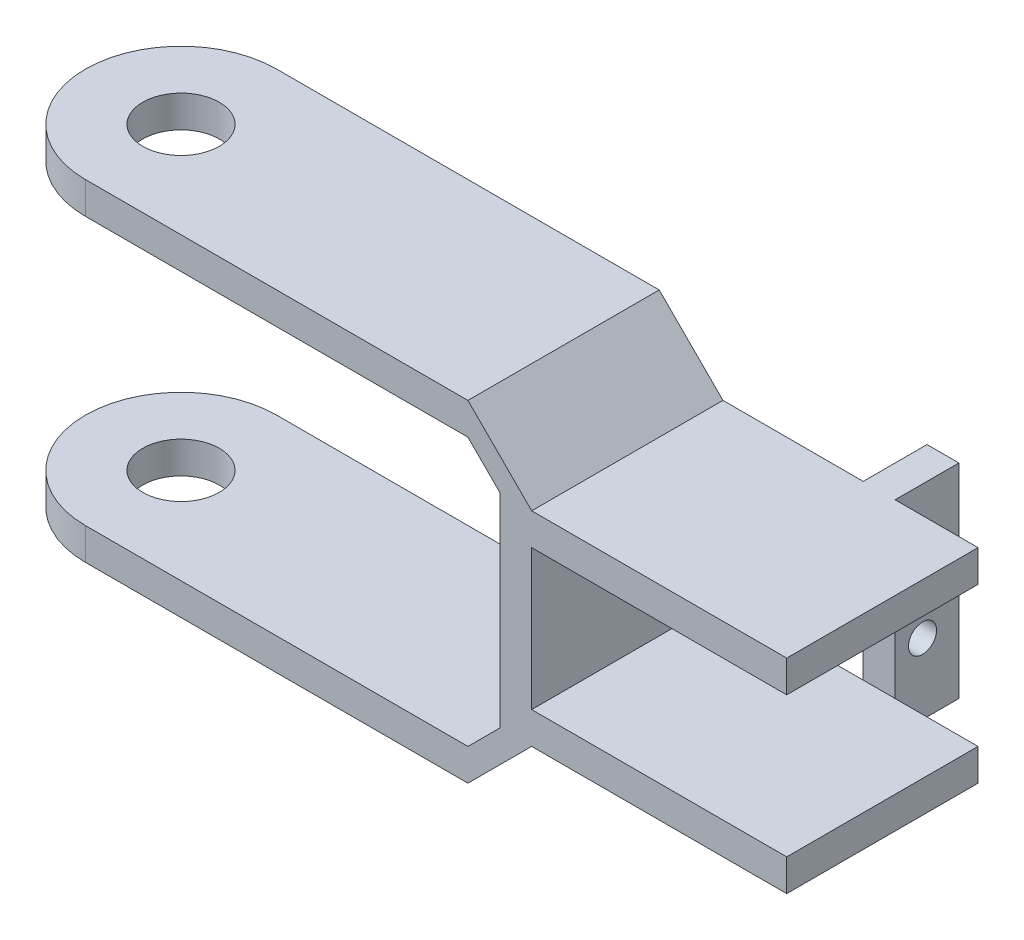
SolidWorks part; units mm, degrees
ref_plane "Front Plane" through (0, 0, 0) normal (0, 0, 1) x (1, 0, 0)
ref_plane "Top Plane" through (0, 0, 0) normal (0, 1, 0) x (1, 0, 0)
ref_plane "Right Plane" through (0, 0, 0) normal (1, 0, 0) x (0, 0, -1)
sketch "Sketch1" plane through (0, 0, 0) normal (0, 1, 0) x (1, 0, 0)
  line L3 (0, 15) -> (60, 15)
  line L4 (0, -15) -> (60, -15)
  line L5 (60, -15) -> (60, 15)
  circle A0 centre (0, 0) radius 6
  arc A2 (0, 15) -> (0, -15) centre (0, 0) ccw
extrude "Boss-Extrude4" add sketch "Sketch1" along normal blind 5
sketch "Sketch8" plane through (0, 0, 15) normal (0, 0, 1) x (1, 0, 0)
  line L0 (0, 0) -> (0, -21) construction
  line L1 (0, -21) -> (118.0272, -21) construction
  line L2 (60, 0) -> (60, -21) construction
  line L3 (60, -21) -> (70, -21) construction
  line L4 (70, -21) -> (70, -10) construction
  line L5 (60, 0) -> (70, -10)
  line L6 (70, -10) -> (110, -10)
  line L7 (110, -10) -> (110, -5)
  line L8 (110, -5) -> (70, -5)
  line L9 (70, -5) -> (60, 5)
  line L10 (60, 5) -> (60, 0)
extrude "Boss-Extrude5" add sketch "Sketch8" against normal blind 30
sketch "Sketch9" plane through (0, 0, 15) normal (0, 0, 1) x (1, 0, 0)
  line L0 (110, -10) -> (110, -21) construction
  line L1 (70, -10) -> (70, -21)
  line L2 (70, -21) -> (65, -21)
  line L3 (65, -21) -> (65, -5)
  line L4 (60, 0) -> (70, -10) construction
  line L5 (65, -5) -> (70, -10)
extrude "Boss-Extrude6" add sketch "Sketch9" against normal blind 30
mirror "Mirror3" about plane through (70, -21, -15) normal (0, -1, 0) of "Boss-Extrude6"
ref_plane "Plane2" through (0, -21, 0) normal (0, -1, 0) x (-1, 0, 0)
sketch "Sketch10" plane through (0, 0, 15) normal (0, 0, 1) x (1, 0, 0)
  line L0 (70, -21) -> (-15.976, -21) construction
  line L1 (70, -32) -> (70, -10) construction
  line L2 (-16.5, -21) -> (16.5, -21) construction
ref_plane "Plane3" through (0, -42, 0) normal (0, -1, 0) x (-1, 0, 0)
sketch "Sketch11" plane through (0, -42, 0) normal (0, -1, 0) x (-1, 0, 0)
  line L0 (0, 15) -> (-60, 15)
  line L1 (-60, 15) -> (-60, -15)
  line L2 (-60, -15) -> (0, -15)
  arc A0 (0, -15) -> (0, 15) centre (0, 0) ccw
  circle A1 centre (0, 0) radius 6
extrude "Boss-Extrude7" add sketch "Sketch11" along normal blind 5 separate body
sketch "Sketch12" plane through (0, 0, -15) normal (0, 0, -1) x (-1, 0, 0)
  line L2 (-70, -10) -> (-110, -10) construction
  line L4 (-110, -5) -> (-70, -5) construction
  line L6 (-70, -5) -> (-60, 5) construction
  line L8 (-60, 0) -> (-65, -5) construction
  line L12 (-16.5, -21) -> (16.5, -21) construction
  line L13 (-70, -32) -> (-65, -37)
  line L14 (-60, -47) -> (-60, -42)
  line L15 (-60, -42) -> (-65, -37)
  line L16 (-70, -37) -> (-60, -47)
  line L17 (-110, -37) -> (-70, -37)
  line L18 (-70, -32) -> (-110, -32)
  line L19 (-110, -32) -> (-110, -37)
extrude "Boss-Extrude8" add sketch "Sketch12" against normal blind 30
sketch "Sketch13" plane through (0, 0, -15) normal (0, 0, -1) x (-1, 0, 0)
  line L0 (-110, -10) -> (-97, -10) construction
  line L1 (-70, -10) -> (-110, -10) construction
  line L2 (-97, -10) -> (-97, -37)
  line L3 (-110, -37) -> (-70, -37) construction
  line L4 (-97, -37) -> (-92, -37)
  line L5 (-92, -37) -> (-92, -5)
  line L6 (-110, -5) -> (-70, -5) construction
  line L7 (-92, -5) -> (-97, -5)
  line L8 (-97, -5) -> (-97, -10)
extrude "Boss-Extrude9" add sketch "Sketch13" along normal blind 10
sketch "Sketch14" plane through (97, 0, 0) normal (1, 0, 0) x (0, 0, -1)
  line L0 (20.5314, -21) -> (19.3, -21) construction
  line L1 (15, -10) -> (15, -32) construction
  line L2 (15, -15) -> (19.3, -15) construction
  line L3 (25, -21) -> (20.5314, -21) construction
  line L4 (25, -5) -> (25, -37) construction
  line L5 (-16.5, -21) -> (16.5, -21) construction
  line L6 (19.3, -21) -> (19.3, -16.05) construction
  circle A2 centre (19.3, -16.05) radius 2.2
  circle A3 centre (19.3, -25.95) radius 2.2
extrude "Cut-Extrude2" cut sketch "Sketch14" against normal up to next
